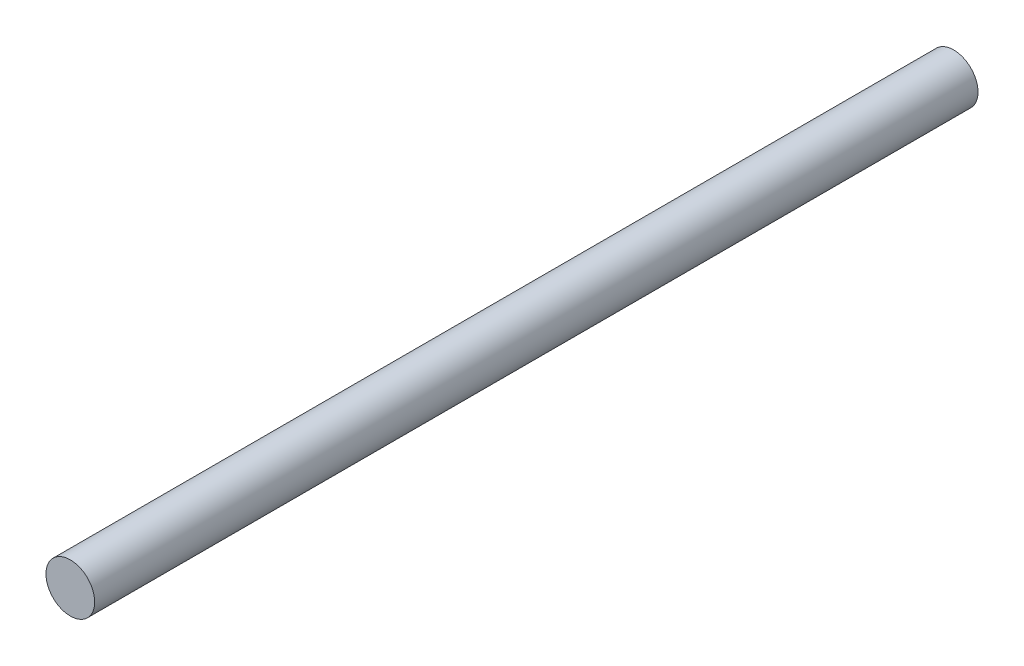
SolidWorks part; units mm, degrees
ref_plane "Front Plane" through (0, 0, 0) normal (0, 0, 1) x (1, 0, 0)
ref_plane "Top Plane" through (0, 0, 0) normal (0, 1, 0) x (1, 0, 0)
ref_plane "Right Plane" through (0, 0, 0) normal (1, 0, 0) x (0, 0, -1)
sketch "Sketch1" plane through (0, 0, 0) normal (0, 0, 1) x (1, 0, 0)
  circle A0 centre (0, 0) radius 4
  dimension "D1" = 8
extrude "Boss-Extrude1" add sketch "Sketch1" along normal blind 145
